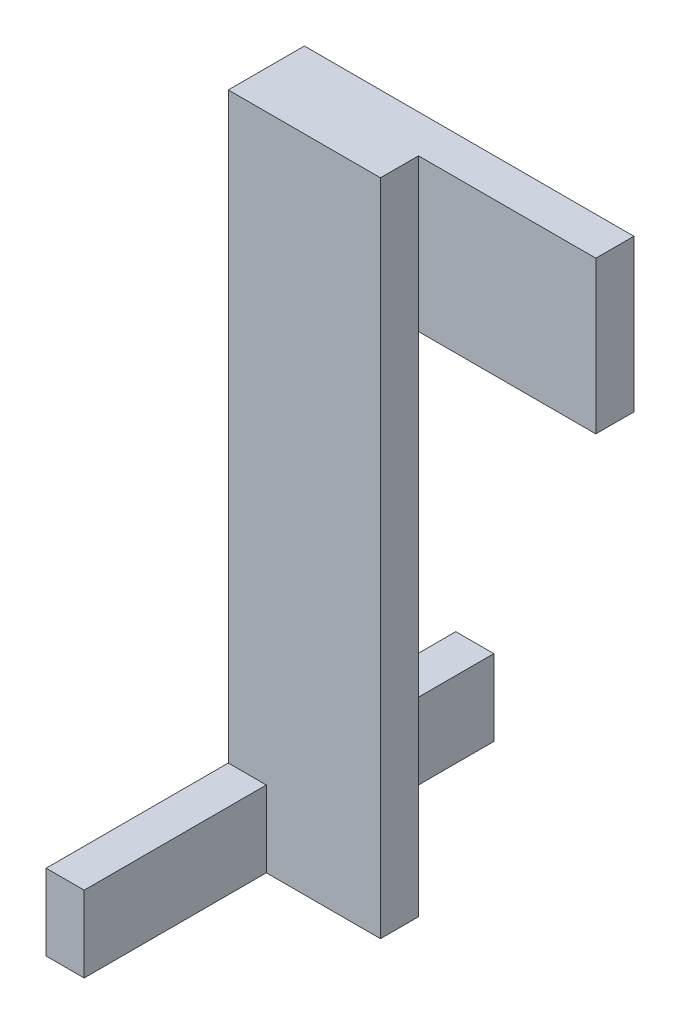
SolidWorks part; units mm, degrees
ref_plane "Alzado" through (0, 0, 0) normal (0, 0, 1) x (1, 0, 0)
ref_plane "Planta" through (0, 0, 0) normal (0, 1, 0) x (1, 0, 0)
ref_plane "Vista lateral" through (0, 0, 0) normal (1, 0, 0) x (0, 0, -1)
sketch "Croquis1" plane through (0, 0, 0) normal (0, 0, 1) x (1, 0, 0)
  line L1 (25.4, -110) -> (-25.4, -110)
  line L2 (25.4, -110) -> (25.4, 110)
  line L3 (25.4, 110) -> (-25.4, 110)
  line L4 (-25.4, -110) -> (-25.4, 110)
  line L5 (25.4, -110) -> (-25.4, 110) construction
  line L6 (25.4, 110) -> (-25.4, -110) construction
  point P0 (0, 0)
  dimension "D1" = 50.8
  dimension "D2" = 220
extrude "Saliente-Extruir1" add sketch "Croquis1" along normal blind 12.7
sketch "Croquis2" plane through (0, 0, 0) normal (0, 0, -1) x (-1, 0, 0)
  line L1 (25.4, 110) -> (-84.6, 110)
  line L2 (25.4, 110) -> (25.4, 59.2)
  line L3 (25.4, 59.2) -> (-84.6, 59.2)
  line L4 (-84.6, 110) -> (-84.6, 59.2)
  dimension "D1" = 50.8
  dimension "D2" = 110
extrude "Saliente-Extruir2" add sketch "Croquis2" along normal blind 12.7
sketch "Croquis3" plane through (-25.4, 0, 0) normal (-1, 0, 0) x (0, 0, 1)
  line L1 (-63.2445, -110) -> (73.5129, -110)
  line L2 (-63.2445, -110) -> (-63.2445, -84.6)
  line L3 (-63.2445, -84.6) -> (73.5129, -84.6)
  line L4 (73.5129, -110) -> (73.5129, -84.6)
  dimension "D1" = 25.4
extrude "Saliente-Extruir3" add sketch "Croquis3" against normal blind 12.7
